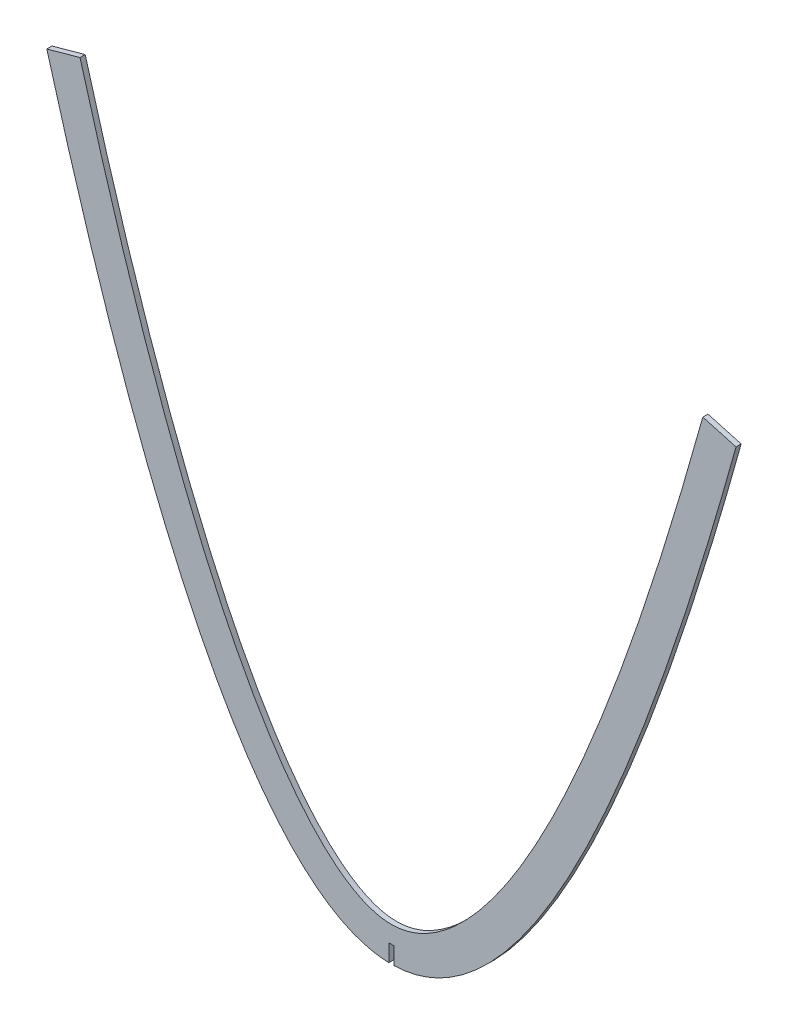
SolidWorks part; units mm, degrees
ref_plane "Front Plane" through (0, 0, 0) normal (0, 0, 1) x (1, 0, 0)
ref_plane "Top Plane" through (0, 0, 0) normal (0, 1, 0) x (1, 0, 0)
ref_plane "Right Plane" through (0, 0, 0) normal (1, 0, 0) x (0, 0, -1)
sketch "Sketch1" plane through (0, 0, 0) normal (0, 0, 1) x (1, 0, 0)
  line L0 (-200, 360) -> (-180.7296, 365.3529)
  line L1 (200, 360) -> (180.7296, 365.3529)
  spline S0 degree 2 poles (-221.8965, 443.1426) (0, -443.1426) (221.8965, 443.1426) knots 0 0 0 1 1 1 construction
  spline S1 degree 2 poles (-200, 360) (0, -360) (200, 360) knots 0.04934 0.04934 0.04934 0.95066 0.95066 0.95066
  spline S2 degree 1 poles (-180.7296, 365.3529) (180.7296, 365.3529) knots 0 0 1 1 construction
  spline S3 degree 2 poles (-180.7296, 365.3529) (-162.1016, 298.3078) (-131.2245, 208.0054) (-106.6867, 147.2908) (-82.4452, 98.2318) (-58.7769, 61.0211) (-39.1311, 39.0211) (-26.2091, 28.8855) (-16.6834, 23.5589) (-8.0324, 20.6686) (0, 19.7771) (8.0324, 20.6686) (16.6834, 23.5589) (26.2091, 28.8855) (39.1311, 39.0211) (58.7769, 61.0211) (82.4452, 98.2318) (106.6867, 147.2908) (131.2245, 208.0054) (162.1016, 298.3078) (180.7296, 365.3529) knots 0.04934 0.04934 0.04934 0.133838 0.190171 0.246503 0.302836 0.359169 0.401418 0.429584 0.457751 0.485917 0.514083 0.542249 0.570416 0.598582 0.640831 0.697164 0.753497 0.809829 0.866162 0.95066 0.95066 0.95066
  dimension "D1" = 20
extrude "Boss-Extrude1" add sketch "Sketch1" along normal blind 3
sketch "Sketch3" plane through (0, 0, 3) normal (0, 0, 1) x (1, 0, 0)
  line L0 (0, 0) -> (-1.5, 0)
  line L1 (-1.5, 0) -> (-1.5, 10)
  line L2 (-1.5, 10) -> (1.5, 10)
  line L3 (1.5, 10) -> (1.5, 0)
  line L4 (1.5, 0) -> (0, 0)
  dimension "D1" = 1.5
  dimension "D2" = 1.5
  dimension "D3" = 10
extrude "Cut-Extrude1" cut sketch "Sketch3" against normal through all
